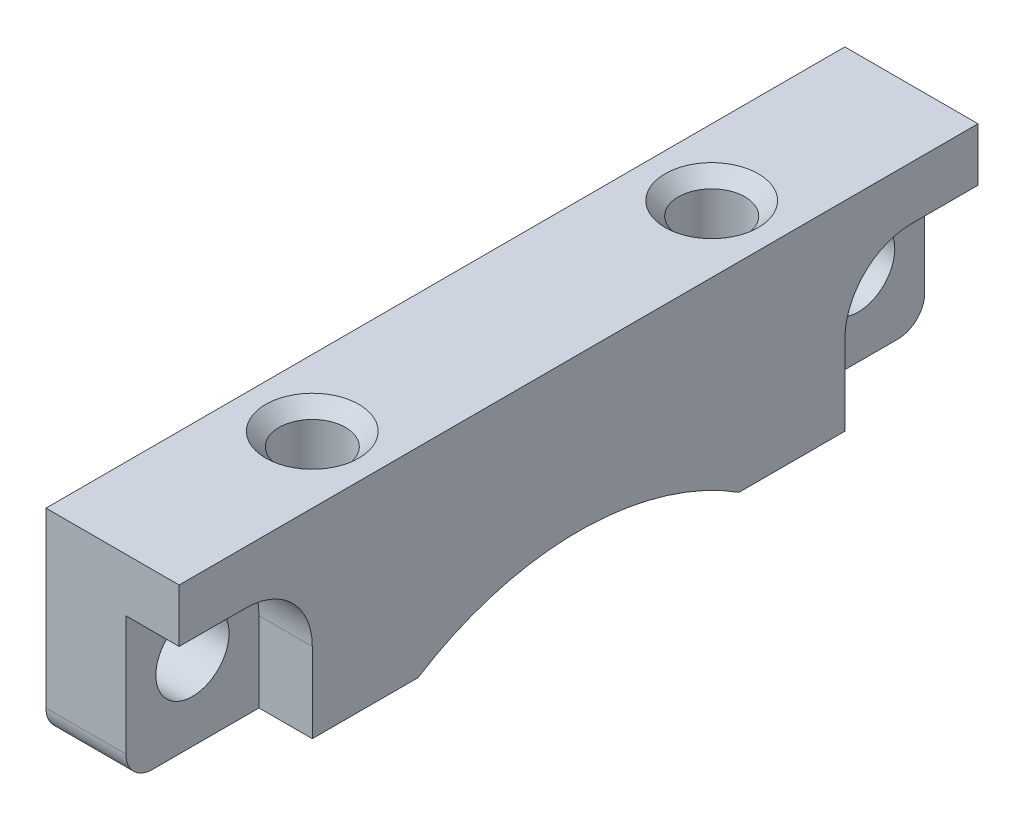
SolidWorks part; units mm, degrees
material "1060 Сплав"
ref_plane "Спереди" through (0, 0, 0) normal (0, 0, 1) x (1, 0, 0)
ref_plane "Сверху" through (0, 0, 0) normal (0, 1, 0) x (1, 0, 0)
ref_plane "Справа" through (0, 0, 0) normal (1, 0, 0) x (0, 0, -1)
sketch "Эскиз7" plane through (0, 0, 0) normal (1, 0, 0) x (0, 0, -1)
  line L1 (30, -30) -> (-30, -30)
  line L2 (30, -30) -> (30, 34)
  line L3 (30, 34) -> (-30, 34)
  line L4 (-30, -30) -> (-30, 34)
  point P0 (0, 0)
  dimension "D1" = 60
  dimension "D2" = 64
  dimension "D3" = 30
  dimension "D4" = 30
extrude "Бобышка-Вытянуть1" add sketch "Эскиз7" along normal blind 10
sketch "Эскиз12" plane through (0, 0, 0) normal (-1, 0, 0) x (0, 0, 1)
  circle A0 centre (0, 0) radius 22.5
  point P2 (14.493, 13.0829)
  dimension "D1" = 45
extrude "Вырез-Вытянуть6" cut sketch "Эскиз12" against normal blind 10
sketch "Эскиз11" plane through (10, 0, 0) normal (1, 0, 0) x (0, 0, -1)
  line L0 (30, 34) -> (-30, 34) construction
  line L1 (-34.79, 19) -> (34.9692, 19)
  line L2 (-34.79, 19) -> (-34.79, -34.9383)
  line L3 (-34.79, -34.9383) -> (34.9692, -34.9383)
  line L4 (34.9692, 19) -> (34.9692, -34.9383)
  dimension "D1" = 15
extrude "Вырез-Вытянуть5" cut sketch "Эскиз11" against normal blind 10
sketch "Эскиз10" plane through (0, 34, 0) normal (0, 1, 0) x (1, 0, 0)
  line L3 (0, 30) -> (0, -30) construction
  point P0 (5, 15)
  point P14 (5, -15)
  dimension "D1" = 5
  dimension "D2" = 15
  dimension "D3" = 30
sketch "Эскиз15" plane through (10, 0, 0) normal (1, 0, 0) x (0, 0, -1)
  line L0 (30, 34) -> (-30, 34) construction
  line L2 (0, 43.2783) -> (0, 21.2433) construction
  point P0 (-25, 25)
  point P2 (25, 25)
  point P17 (0, 0)
  dimension "D1" = 9
  dimension "D2" = 50
hole_wizard "Сверло под метчик  спиральное M51" positions "Эскиз15" profile "Эскиз14" hole size "M5x0.8" standard "DIN" end condition through all
sketch "Эскиз14" plane through (10, 25, 25) normal (0, 1, 0) x (0, 0, -1)
  line L0 (0, 0) -> (0, 10)
  line L1 (0, 10) -> (2.75, 10)
  line L2 (2.75, 10) -> (2.75, 0)
  line L5 (2.75, 0) -> (0, 0)
  line L11 (0, -6.35) -> (0, 107.95) construction
  dimension "Диаметр сквозного отверстия" = 5.5
  dimension "Глубина сквозного отверстия" = 10
hole_wizard "Отверстие обработанное метчиком M61" positions "Эскиз10" profile "Эскиз9" tap size "M6" standard "IS" end condition through all
cosmetic thread "Отверстие резьбы1" parameters "D2"=6
cosmetic thread "Отверстие резьбы2" parameters "D2"=6
sketch "Эскиз9" plane through (5, 34, -15) normal (1, 0, 0) x (0, 0, 1)
  line L0 (0, 0) -> (0, 15)
  line L1 (0, 15) -> (2.5, 15)
  line L2 (2.5, 15) -> (2.5, 1)
  line L3 (2.5, 1) -> (3.5, 0)
  line L5 (3.5, 0) -> (0, 0)
  line L6 (-2.5, 1) -> (-3.5, 0) construction
  line L11 (0, -6.35) -> (0, 107.95) construction
  dimension "Диаметр проходного сверла" = 5
  dimension "Глубина проходного сверла" = 15
  dimension "Диаметр передней зенковки" = 7
  dimension "Угол передней зенковки" = 90
sketch "Эскиз16" plane through (10, 0, 0) normal (1, 0, 0) x (0, 0, -1)
  line L0 (-25, 30) -> (-30, 30)
  line L1 (-30, 30) -> (-30, 19)
  line L3 (-20, 19) -> (-30, 19)
  line L4 (-20, 25) -> (-20, 19)
  line L5 (-30, 34) -> (-30, 19) construction
  line L6 (-17.5, 19) -> (-12.5, 19) construction
  line L7 (0, 38.87) -> (0, 19.8885) construction
  line L8 (20, 25) -> (20, 19)
  line L9 (20, 19) -> (30, 19)
  line L10 (30, 30) -> (30, 19)
  line L11 (25, 30) -> (30, 30)
  arc A0 (-20, 25) -> (-25, 30) centre (-25, 25) ccw
  circle A1 centre (-25, 25) radius 2.75 construction
  arc A2 (20, 25) -> (25, 30) centre (25, 25) cw
  dimension "D1" = 5
extrude "Вырез-Вытянуть7" cut sketch "Эскиз16" against normal blind 4
fillet "Скругление1" radius 2 2 edges at (3, 19, -30) (3, 19, 30)
